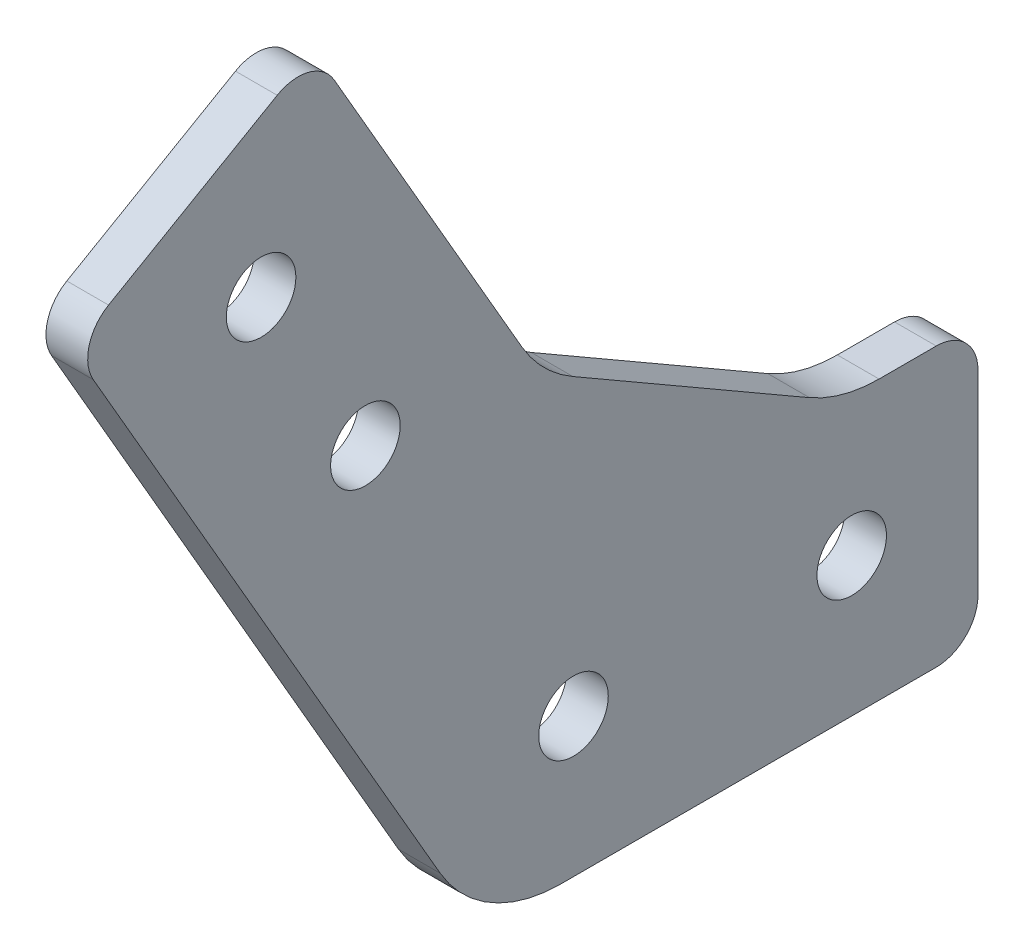
SolidWorks part; units mm, degrees
material "Thornel VCB-20 Carbon Cloth"
ref_plane "Front Plane" through (0, 0, 0) normal (0, 0, 1) x (1, 0, 0)
ref_plane "Top Plane" through (0, 0, 0) normal (0, 1, 0) x (1, 0, 0)
ref_plane "Right Plane" through (0, 0, 0) normal (1, 0, 0) x (0, 0, -1)
sketch "Sketch1" plane through (0, 0, 0) normal (1, 0, 0) x (0, 0, -1)
  line L0 (0, 0) -> (91.4792, 0) construction
  line L1 (0, 0) -> (-51.5685, 89.3193) construction
  line L2 (22.8868, 10) -> (30, 10)
  line L3 (-2.7831, 24.8205) -> (-17.7831, 50.8013)
  line L4 (0, -10) -> (30, -10)
  line L5 (-8.6603, -5) -> (-35.1036, 40.8013)
  line L6 (0.8771, 21.1603) -> (17.8868, 11.3397)
  line L7 (-35.1036, 40.8013) -> (-17.7831, 50.8013)
  line L8 (30, 10) -> (30, -10)
  line L10 (5.7735, 10) -> (-42.9083, 94.3193) construction
  line L11 (-5.7735, -10) -> (-60.2288, 84.3193) construction
  line L12 (5.7735, 10) -> (91.4792, 10) construction
  line L13 (-5.7735, -10) -> (91.4792, -10) construction
  arc A0 (22.8868, 10) -> (17.8868, 11.3397) centre (22.8868, 20) cw
  arc A1 (0.8771, 21.1603) -> (-2.7831, 24.8205) centre (5.8771, 29.8205) cw
  arc A2 (0, -10) -> (-8.6603, -5) centre (0, 0) cw
  point P18 (20.2073, 10)
  point P21 (-1.4434, 22.5)
  dimension "D6" = 10
  dimension "D1" = 120
  dimension "D4" = 30
  dimension "D5" = 25
  dimension "D7" = 30
  dimension "D8" = 30
  dimension "D2" = 10
  dimension "D3" = 10
extrude "Boss-Extrude1" add sketch "Sketch1" along normal blind 3
sketch "Sketch2" plane through (3, 0, 0) normal (1, 0, 0) x (0, 0, -1)
  line L0 (32.9012, 0) -> (-17.4104, 0) construction
  line L1 (30, -10) -> (30, 10) construction
  line L2 (0, -10) -> (30, -10) construction
  circle A0 centre (20.92, 0) radius 2.5
  circle A2 centre (0.92, 0) radius 2.5
  circle A3 centre (-14.04, 24.32) radius 2.5
  circle A4 centre (-21.54, 37.31) radius 2.5
  dimension "D1" = 5
  dimension "D2" = 5
  dimension "D5" = 5
  dimension "D6" = 5
  dimension "D3" = 9.08
  dimension "D4" = 29.08
  dimension "D7" = 34.32
  dimension "D8" = 14.04
  dimension "D9" = 47.31
  dimension "D10" = 21.54
extrude "Cut-Extrude1" cut sketch "Sketch2" against normal through all
fillet "Fillet1" radius 3 4 edges at (1.5, 40.8013, 35.1036) (1.5, -10, -30) (1.5, 10, -30) (1.5, 50.8013, 17.7831)
